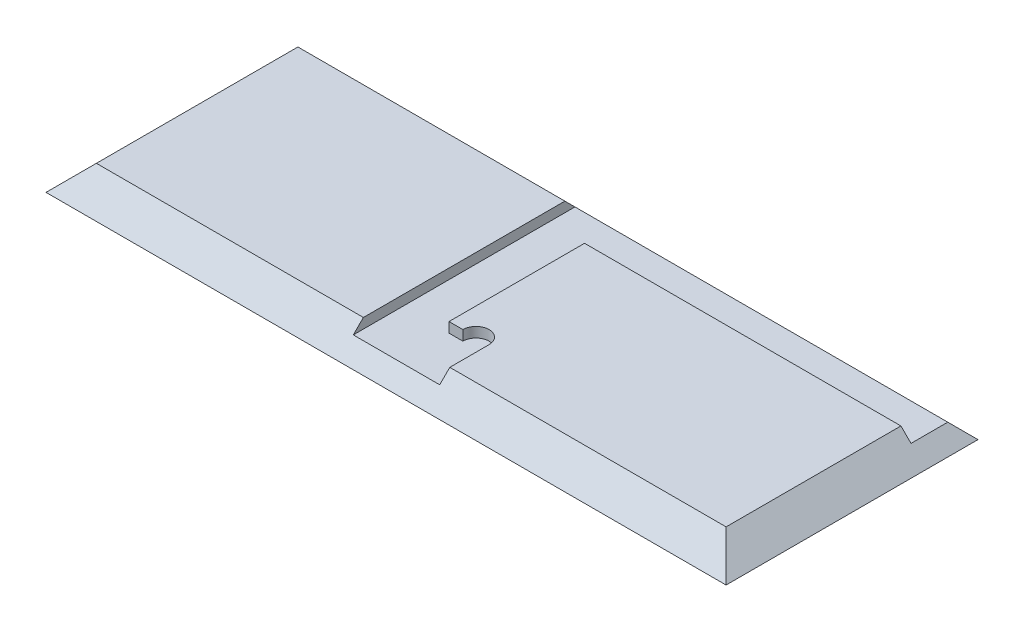
SolidWorks part; units mm, degrees
ref_plane "Front Plane" through (0, 0, 0) normal (0, 0, 1) x (1, 0, 0)
ref_plane "Top Plane" through (0, 0, 0) normal (0, 1, 0) x (1, 0, 0)
ref_plane "Right Plane" through (0, 0, 0) normal (1, 0, 0) x (0, 0, -1)
sketch "Sketch1" plane through (0, 0, 0) normal (0, 1, 0) x (1, 0, 0)
  line L1 (-171.45, 63.5) -> (171.45, 63.5)
  line L2 (-171.45, 63.5) -> (-171.45, -63.5)
  line L3 (-171.45, -63.5) -> (171.45, -63.5)
  line L4 (171.45, 63.5) -> (171.45, -63.5)
  line L8 (-171.45, 63.5) -> (171.45, -63.5) construction
  line L9 (-171.45, 63.5) -> (-171.45, -63.5) construction
  line L10 (-171.45, 63.5) -> (171.45, 63.5) construction
extrude "Boss-Extrude1" add sketch "Sketch1" along normal blind 12.7
draft "Draft1" type of draft neutral plane draft angle 45 faces to draft 4 face at (0, 6.35, -63.5) face at (-171.45, 6.35, 0) face at (171.45, 6.35, 0) face at (0, 6.35, 63.5) neutral plane through (0, 0, 0) neutral plane normal (0, -1, 0) reverse direction yes parameters "D1"=45
sketch "Sketch2" plane through (0, 12.7, 0) normal (0, 1, 0) x (1, 0, 0)
  line L0 (-171.45, -63.5) -> (171.45, -63.5) construction
  line L1 (-19.431, -63.5) -> (19.431, -63.5)
  line L2 (-19.431, -63.5) -> (-19.431, -30.988)
  line L3 (-6.223, -30.988) -> (6.223, -30.988)
  line L5 (0, 0) -> (0, 50.8) construction
  line L6 (158.75, 50.8) -> (-158.75, 50.8) construction
  line L7 (19.431, -63.5) -> (19.431, -30.988)
  line L10 (-19.05, -50.419) -> (-19.05, -31.369) construction
  line L11 (19.05, -31.369) -> (-19.05, -31.369) construction
  arc A0 (-19.431, -30.988) -> (-6.223, -30.988) centre (-12.827, -30.988) cw
  arc A1 (19.431, -30.988) -> (6.223, -30.988) centre (12.827, -30.988) ccw
  dimension "D1" = 6.604
  dimension "D2" = 0.381
  dimension "D3" = 0.381
extrude "Cut-Extrude1" cut sketch "Sketch2" against normal blind 5.08
sketch "Sketch3" plane through (0, 12.7, 0) normal (0, 1, 0) x (1, 0, 0)
  line L0 (171.45, 63.5) -> (-171.45, 63.5) construction
  line L1 (-24.13, 63.5) -> (-0.762, 63.5)
  line L2 (-24.13, 63.5) -> (-24.13, -63.5)
  line L3 (-24.13, -63.5) -> (-0.762, -63.5)
  line L4 (-0.762, 63.5) -> (-0.762, -63.5)
  line L5 (-171.45, -63.5) -> (171.45, -63.5) construction
  line L8 (-171.45, 63.5) -> (-171.45, -63.5) construction
  dimension "D1" = 23.368
  dimension "D2" = 170.688
extrude "Cut-Extrude2" cut sketch "Sketch3" against normal blind 5.08
sketch "Sketch4" plane through (0, 12.7, 0) normal (0, 1, 0) x (1, 0, 0)
  line L1 (171.45, 63.5) -> (-0.762, 63.5)
  line L2 (171.45, 63.5) -> (171.45, 37.338)
  line L3 (171.45, 37.338) -> (-0.762, 37.338)
  line L5 (163.449, 37.719) -> (150.8766, 37.719) construction
  line L6 (-0.762, -30.988) -> (-0.762, 50.8) construction
  line L7 (-0.762, 37.338) -> (-0.762, 63.5)
  line L8 (171.45, 63.5) -> (-171.45, 63.5) construction
  dimension "D1" = 0.381
extrude "Cut-Extrude3" cut sketch "Sketch4" against normal blind 5.08
